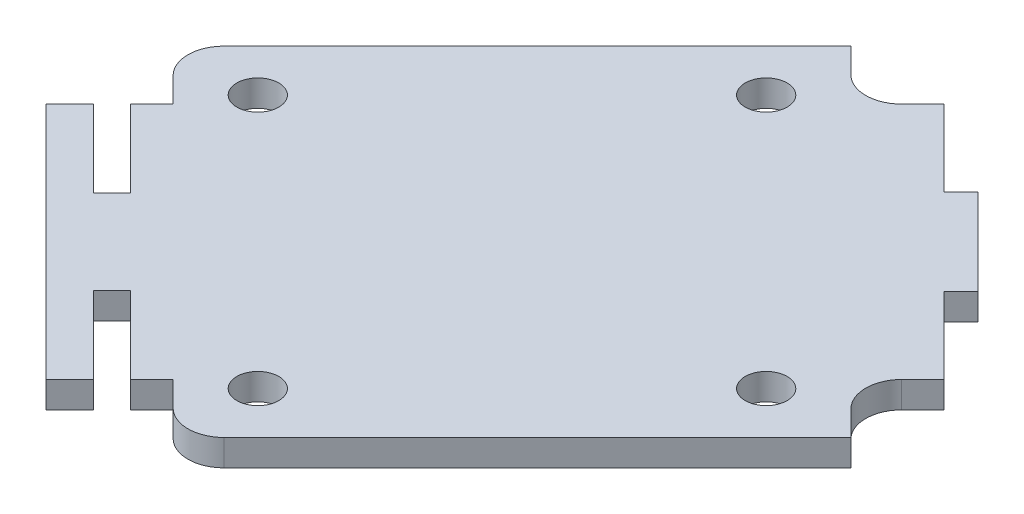
SolidWorks part; units mm, degrees
material "cardboard"
ref_plane "Front Plane" through (0, 0, 0) normal (0, 0, 1) x (1, 0, 0)
ref_plane "Top Plane" through (0, 0, 0) normal (0, 1, 0) x (1, 0, 0)
ref_plane "Right Plane" through (0, 0, 0) normal (1, 0, 0) x (0, 0, -1)
sketch "Sketch1" plane through (0, 0, 0) normal (0, 1, 0) x (1, 0, 0)
  line L0 (-132.1728, 126.9012) -> (-121.1728, 126.9012)
  line L1 (-122.1728, 122.9012) -> (-122.1728, 106.9012)
  line L2 (-62.3728, 122.9012) -> (-62.3728, 106.9012)
  line L3 (-119.7728, 106.9012) -> (-122.1728, 106.9012)
  line L4 (-133.5728, 122.9012) -> (-131.1728, 122.9012)
  line L5 (-133.5728, 122.9012) -> (-133.5728, 106.9012)
  line L6 (-133.5728, 106.9012) -> (-131.1728, 106.9012)
  line L7 (-131.1728, 122.9012) -> (-131.1728, 106.9012)
  line L8 (-119.7728, 122.9012) -> (-119.7728, 106.9012)
  line L9 (-119.7728, 122.9012) -> (-122.1728, 122.9012)
  line L10 (-59.9728, 122.9012) -> (-59.9728, 106.9012)
  line L11 (-96.5728, 126.9012) -> (-85.5728, 126.9012)
  line L12 (-62.3728, 122.9012) -> (-59.9728, 122.9012)
  line L13 (-62.3728, 106.9012) -> (-59.9728, 106.9012)
  line L14 (-50.9728, 122.9012) -> (-50.9728, 106.9012)
  line L15 (-48.5728, 122.9012) -> (-50.9728, 122.9012)
  line L16 (-48.5728, 122.9012) -> (-48.5728, 106.9012)
  line L17 (-48.5728, 106.9012) -> (-50.9728, 106.9012)
  line L18 (8.8272, 122.9012) -> (8.8272, 106.9012)
  line L19 (11.2272, 122.9012) -> (11.2272, 106.9012)
  line L20 (8.8272, 122.9012) -> (11.2272, 122.9012)
  line L21 (8.8272, 106.9012) -> (11.2272, 106.9012)
  line L22 (20.2272, 122.9012) -> (20.2272, 106.9012)
  line L23 (22.6272, 122.9012) -> (20.2272, 122.9012)
  line L24 (22.6272, 122.9012) -> (22.6272, 106.9012)
  line L25 (22.6272, 106.9012) -> (20.2272, 106.9012)
  line L26 (80.0272, 122.9012) -> (80.0272, 106.9012)
  line L27 (82.4272, 122.9012) -> (82.4272, 106.9012)
  line L28 (-60.9728, 126.9012) -> (-49.9728, 126.9012)
  line L29 (80.0272, 122.9012) -> (82.4272, 122.9012)
  line L30 (80.0272, 106.9012) -> (82.4272, 106.9012)
  line L31 (91.4272, 122.9012) -> (91.4272, 106.9012)
  line L32 (56.8272, 128.9012) -> (81.4272, 128.9012)
  line L33 (93.8272, 122.9012) -> (91.4272, 122.9012)
  line L34 (93.8272, 122.9012) -> (93.8272, 106.9012)
  line L35 (93.8272, 106.9012) -> (91.4272, 106.9012)
  line L36 (62.8843, 36.8646) -> (69.3002, 30.4488)
  line L37 (82.7871, 16.9619) -> (84.767, 18.9418)
  line L38 (62.8843, 36.8646) -> (64.8642, 38.8445)
  line L39 (76.3712, 23.3777) -> (82.7871, 16.9619)
  line L40 (82.7871, -85.8891) -> (76.3712, -92.305)
  line L41 (82.7871, -85.8891) -> (84.767, -87.869)
  line L42 (84.767, -87.869) -> (64.8642, -107.7718)
  line L43 (62.8843, -105.7919) -> (64.8642, -107.7718)
  line L44 (69.3002, -99.376) -> (62.8843, -105.7919)
  line L45 (-39.9666, -105.7919) -> (-46.3825, -99.376)
  line L46 (-39.9666, -105.7919) -> (-41.9465, -107.7718)
  line L47 (-41.9465, -107.7718) -> (-61.8493, -87.869)
  line L48 (-59.8694, -85.8891) -> (-61.8493, -87.869)
  line L49 (-53.4536, -92.305) -> (-59.8694, -85.8891)
  line L50 (-25.3728, 126.9012) -> (-14.3728, 126.9012)
  line L51 (10.2272, 126.9012) -> (21.2272, 126.9012)
  line L52 (45.8272, 126.9012) -> (56.8272, 126.9012)
  line L53 (81.4272, 126.9012) -> (92.4272, 126.9012)
  line L54 (117.0272, 126.9012) -> (128.0272, 126.9012)
  line L55 (-36.6432, -102.4685) -> (-34.5738, -104.5379)
  line L56 (-6.2376, -76.3055) -> (-4.1682, -78.3749)
  line L57 (-56.546, -82.5657) -> (-58.3138, -84.3335)
  line L58 (-36.6432, -102.4685) -> (-38.411, -104.2362)
  line L59 (-32.4525, -50.0907) -> (-58.6154, -76.2536)
  line L60 (-58.6154, -80.4963) -> (-56.546, -82.5657)
  line L61 (-4.1682, -78.3749) -> (-30.3312, -104.5379)
  line L62 (-32.4525, -50.0907) -> (-30.3831, -52.1601)
  line L63 (-144.4728, 128.9012) -> (-132.1728, 128.9012)
  line L64 (-55.8571, 81.6029) -> (-55.8571, 86.6029)
  line L65 (-65.8571, 81.6029) -> (-65.8571, 86.6029)
  line L66 (-35.3072, 73.0909) -> (-31.7716, 76.6264)
  line L67 (-28.2361, 66.0198) -> (-24.7006, 69.5553)
  line L68 (-19.724, 45.4699) -> (-14.724, 45.4699)
  line L69 (-19.724, 35.4699) -> (-14.724, 35.4699)
  line L70 (-28.2361, 14.92) -> (-24.7006, 11.3845)
  line L71 (-35.3072, 7.8489) -> (-31.7716, 4.3134)
  line L72 (-55.8571, -0.6631) -> (-55.8571, -5.6631)
  line L73 (-65.8571, -0.6631) -> (-65.8571, -5.6631)
  line L74 (-86.407, 7.8489) -> (-89.9425, 4.3134)
  line L75 (61.3287, 35.309) -> (67.7445, 28.8931)
  line L76 (74.8156, 21.8221) -> (81.2315, 15.4062)
  line L77 (74.8156, 21.8221) -> (76.3712, 23.3777)
  line L78 (67.7445, 28.8931) -> (69.3002, 30.4488)
  line L79 (29.5322, -78.0966) -> (32.3607, -75.2682)
  line L80 (55.0919, -16.3902) -> (52.2634, -13.5618)
  line L81 (-144.4728, 128.9012) -> (-144.4728, 118.9012)
  line L82 (-6.6146, 9.1694) -> (-32.1742, -16.3902)
  line L83 (-144.4728, 100.9012) -> (-128.6728, 100.9012)
  line L84 (-93.4781, 14.92) -> (-97.0136, 11.3845)
  line L85 (-108.8728, 119.9012) -> (-108.8728, 109.9012)
  line L86 (64.8642, 38.8445) -> (84.767, 18.9418)
  line L87 (-22.9584, -48.9781) -> (-3.0557, -68.8809)
  line L88 (-22.9584, -48.9781) -> (-26.1404, -52.1601)
  line L89 (-3.0557, -68.8809) -> (-6.2376, -72.0629)
  line L90 (-32.1742, -16.3902) -> (-67.1742, -16.3902)
  line L91 (-82.1742, -31.3902) -> (-82.1742, -37.537)
  line L92 (-67.1742, -52.537) -> (-34.8988, -52.537)
  line L93 (-112.1728, 105.9012) -> (-114.6728, 105.9012)
  line L94 (-141.1728, 125.9012) -> (-138.6728, 125.9012)
  line L95 (-141.1728, 125.9012) -> (-141.1728, 105.9012)
  line L96 (-141.1728, 105.9012) -> (-138.6728, 105.9012)
  line L97 (-138.6728, 125.9012) -> (-138.6728, 105.9012)
  line L98 (-114.6728, 125.9012) -> (-114.6728, 105.9012)
  line L99 (29.5322, 9.1694) -> (29.5322, 44.1694)
  line L100 (14.5322, 59.1694) -> (8.3854, 59.1694)
  line L101 (-6.6146, 44.1694) -> (-6.6146, 9.1694)
  line L102 (-112.1728, 125.9012) -> (-114.6728, 125.9012)
  line L103 (-112.1728, 125.9012) -> (-112.1728, 105.9012)
  line L104 (-124.6728, 100.9012) -> (-110.3728, 100.9012)
  line L105 (-108.8728, 119.9012) -> (-108.8728, 109.9012)
  line L106 (55.0919, -52.537) -> (90.0919, -52.537)
  line L107 (105.0919, -37.537) -> (105.0919, -31.3902)
  line L108 (90.0919, -16.3902) -> (55.0919, -16.3902)
  line L109 (-74.7728, 100.9012) -> (-73.2728, 100.9012)
  line L110 (-73.2728, 128.9012) -> (-73.2728, 100.9012)
  line L111 (21.2272, 128.9012) -> (45.8272, 128.9012)
  line L112 (-73.2728, 128.9012) -> (-73.2728, 100.9012)
  line L113 (-73.2728, 100.9012) -> (-37.6728, 100.9012)
  line L114 (-37.6728, 128.9012) -> (-37.6728, 100.9012)
  line L115 (-6.6146, -80.8213) -> (-6.6146, -113.0966)
  line L116 (8.3854, -128.0966) -> (14.5322, -128.0966)
  line L117 (29.5322, -113.0966) -> (29.5322, -78.0966)
  line L118 (-14.3728, 128.9012) -> (10.2272, 128.9012)
  line L119 (-37.6728, 128.9012) -> (-37.6728, 100.9012)
  line L120 (-37.6728, 100.9012) -> (-2.0728, 100.9012)
  line L121 (-2.0728, 128.9012) -> (-2.0728, 100.9012)
  line L122 (-49.9728, 128.9012) -> (-25.3728, 128.9012)
  line L123 (-2.0728, 128.9012) -> (-2.0728, 100.9012)
  line L124 (52.2634, -55.3654) -> (55.0919, -52.537)
  line L125 (25.9733, -68.8809) -> (45.8761, -48.9781)
  line L126 (81.2315, -84.3335) -> (74.8156, -90.7493)
  line L127 (45.8761, -48.9781) -> (81.2315, -84.3335)
  line L128 (74.8156, -90.7493) -> (76.3712, -92.305)
  line L129 (78.3511, -94.2849) -> (71.2801, -101.3559)
  line L130 (25.9733, -68.8809) -> (61.3287, -104.2362)
  line L131 (67.7445, -97.8204) -> (69.3002, -99.376)
  line L132 (67.7445, -97.8204) -> (61.3287, -104.2362)
  line L133 (-38.411, -104.2362) -> (-44.8269, -97.8204)
  line L134 (-44.8269, -97.8204) -> (-46.3825, -99.376)
  line L135 (32.3607, 6.341) -> (29.5322, 9.1694)
  line L136 (-101.9901, 35.4699) -> (-106.9901, 35.4699)
  line L137 (45.8761, -19.9491) -> (25.9733, -0.0463)
  line L138 (45.8761, -19.9491) -> (81.2315, 15.4062)
  line L139 (25.9733, -0.0463) -> (61.3287, 35.309)
  line L140 (-48.3624, -101.3559) -> (-55.4335, -94.2849)
  line L141 (-51.8979, -90.7493) -> (-53.4536, -92.305)
  line L142 (-51.8979, -90.7493) -> (-58.3138, -84.3335)
  line L143 (-65.8571, 81.6029) -> (-77.8949, 81.6029)
  line L144 (-77.8949, 81.6029) -> (-86.407, 73.0909)
  line L145 (-2.0728, 100.9012) -> (33.5272, 100.9012)
  line L146 (33.5272, 128.9012) -> (33.5272, 100.9012)
  line L147 (-85.5728, 128.9012) -> (-60.9728, 128.9012)
  line L148 (33.5272, 128.9012) -> (33.5272, 100.9012)
  line L149 (33.5272, 100.9012) -> (69.1272, 100.9012)
  line L150 (69.1272, 128.9012) -> (69.1272, 100.9012)
  line L151 (-121.1728, 128.9012) -> (-110.3728, 128.9012)
  line L152 (69.1272, 128.9012) -> (69.1272, 100.9012)
  line L153 (69.1272, 100.9012) -> (104.7272, 100.9012)
  line L154 (104.7272, 128.9012) -> (104.7272, 100.9012)
  line L155 (128.0272, 128.9012) -> (140.3272, 128.9012)
  line L156 (104.7272, 128.9012) -> (104.7272, 100.9012)
  line L157 (104.7272, 100.9012) -> (140.3272, 100.9012)
  line L158 (140.3272, 128.9012) -> (140.3272, 118.9012)
  line L159 (-69.9728, 125.9012) -> (-67.4728, 125.9012)
  line L160 (-69.9728, 125.9012) -> (-69.9728, 105.9012)
  line L161 (-69.9728, 105.9012) -> (-67.4728, 105.9012)
  line L162 (-67.4728, 125.9012) -> (-67.4728, 105.9012)
  line L163 (-43.4728, 125.9012) -> (-43.4728, 105.9012)
  line L164 (-40.9728, 105.9012) -> (-43.4728, 105.9012)
  line L165 (-40.9728, 125.9012) -> (-40.9728, 105.9012)
  line L166 (-40.9728, 125.9012) -> (-43.4728, 125.9012)
  line L167 (-61.4728, 100.9012) -> (-61.4728, 96.9012)
  line L168 (-61.4728, 96.9012) -> (-49.4728, 96.9012)
  line L169 (-49.4728, 96.9012) -> (-49.4728, 100.9012)
  line L170 (1.2272, 125.9012) -> (3.7272, 125.9012)
  line L171 (1.2272, 125.9012) -> (1.2272, 105.9012)
  line L172 (1.2272, 105.9012) -> (3.7272, 105.9012)
  line L173 (3.7272, 125.9012) -> (3.7272, 105.9012)
  line L174 (27.7272, 125.9012) -> (27.7272, 105.9012)
  line L175 (30.2272, 105.9012) -> (27.7272, 105.9012)
  line L176 (30.2272, 125.9012) -> (30.2272, 105.9012)
  line L177 (30.2272, 125.9012) -> (27.7272, 125.9012)
  line L178 (9.7272, 100.9012) -> (9.7272, 96.9012)
  line L179 (9.7272, 96.9012) -> (21.7272, 96.9012)
  line L180 (21.7272, 96.9012) -> (21.7272, 100.9012)
  line L181 (72.4272, 125.9012) -> (74.9272, 125.9012)
  line L182 (72.4272, 125.9012) -> (72.4272, 105.9012)
  line L183 (72.4272, 105.9012) -> (74.9272, 105.9012)
  line L184 (74.9272, 125.9012) -> (74.9272, 105.9012)
  line L185 (98.9272, 125.9012) -> (98.9272, 105.9012)
  line L186 (101.4272, 105.9012) -> (98.9272, 105.9012)
  line L187 (101.4272, 125.9012) -> (101.4272, 105.9012)
  line L188 (101.4272, 125.9012) -> (98.9272, 125.9012)
  line L189 (80.9272, 100.9012) -> (80.9272, 96.9012)
  line L190 (80.9272, 96.9012) -> (92.9272, 96.9012)
  line L191 (92.9272, 96.9012) -> (92.9272, 100.9012)
  line L192 (-128.6728, 100.9012) -> (-128.6728, 101.9012)
  line L193 (-128.6728, 101.9012) -> (-124.6728, 101.9012)
  line L194 (-124.6728, 101.9012) -> (-124.6728, 100.9012)
  line L195 (-61.4728, 99.9012) -> (-57.4728, 99.9012)
  line L196 (-57.4728, 99.9012) -> (-57.4728, 101.9012)
  line L197 (-57.4728, 101.9012) -> (-53.4728, 101.9012)
  line L198 (-53.4728, 101.9012) -> (-53.4728, 99.9012)
  line L199 (-53.4728, 99.9012) -> (-49.4728, 99.9012)
  line L200 (9.7272, 99.9012) -> (13.7272, 99.9012)
  line L201 (13.7272, 99.9012) -> (13.7272, 101.9012)
  line L202 (13.7272, 101.9012) -> (17.7272, 101.9012)
  line L203 (27.3876, 1.3679) -> (33.7515, -4.9961)
  line L204 (33.7515, -4.9961) -> (30.9231, -7.8245)
  line L205 (30.9231, -7.8245) -> (38.098, -14.9994)
  line L206 (38.098, -14.9994) -> (40.9264, -12.1709)
  line L207 (40.9264, -12.1709) -> (47.2903, -18.5349)
  line L208 (47.2903, -50.3923) -> (40.9264, -56.7563)
  line L209 (40.9264, -56.7563) -> (38.098, -53.9279)
  line L210 (38.098, -53.9279) -> (30.9231, -61.1027)
  line L211 (30.9231, -61.1027) -> (33.7515, -63.9312)
  line L212 (33.7515, -63.9312) -> (27.3876, -70.2951)
  line L213 (-4.4699, -70.2951) -> (-10.8338, -63.9312)
  line L214 (-10.8338, -63.9312) -> (-8.0054, -61.1027)
  line L215 (-8.0054, -61.1027) -> (-15.1803, -53.9279)
  line L216 (-15.1803, -53.9279) -> (-18.0087, -56.7563)
  line L217 (-18.0087, -56.7563) -> (-24.3727, -50.3923)
  line L218 (-89.9425, 76.6264) -> (-97.0136, 69.5553)
  line L219 (-93.4781, 66.0198) -> (-101.9901, 57.5078)
  line L220 (-101.9901, 57.5078) -> (-101.9901, 45.4699)
  line L221 (-106.9901, 45.4699) -> (-106.9901, 35.4699)
  line L222 (-101.9901, 35.4699) -> (-101.9901, 23.432)
  line L223 (-101.9901, 23.432) -> (-93.4781, 14.92)
  line L224 (-97.0136, 11.3845) -> (-89.9425, 4.3134)
  line L225 (-86.407, 7.8489) -> (-77.8949, -0.6631)
  line L226 (-77.8949, -0.6631) -> (-65.8571, -0.6631)
  line L227 (-65.8571, -5.6631) -> (-55.8571, -5.6631)
  line L228 (-55.8571, -0.6631) -> (-43.8192, -0.6631)
  line L229 (-43.8192, -0.6631) -> (-35.3072, 7.8489)
  line L230 (-31.7716, 4.3134) -> (-24.7006, 11.3845)
  line L231 (-28.2361, 14.92) -> (-19.724, 23.432)
  line L232 (-19.724, 23.432) -> (-19.724, 35.4699)
  line L233 (-14.724, 35.4699) -> (-14.724, 45.4699)
  line L234 (-19.724, 45.4699) -> (-19.724, 57.5078)
  line L235 (-19.724, 57.5078) -> (-28.2361, 66.0198)
  line L236 (-24.7006, 69.5553) -> (-31.7716, 76.6264)
  line L237 (-35.3072, 73.0909) -> (-43.8192, 81.6029)
  line L238 (-43.8192, 81.6029) -> (-55.8571, 81.6029)
  line L239 (-55.8571, 86.6029) -> (-65.8571, 86.6029)
  line L240 (-101.9901, 45.4699) -> (-106.9901, 45.4699)
  line L241 (-93.4781, 66.0198) -> (-97.0136, 69.5553)
  line L242 (-86.407, 73.0909) -> (-89.9425, 76.6264)
  line L243 (17.7272, 101.9012) -> (17.7272, 99.9012)
  line L244 (17.7272, 99.9012) -> (21.7272, 99.9012)
  line L245 (80.9272, 99.9012) -> (84.9272, 99.9012)
  line L246 (84.9272, 99.9012) -> (84.9272, 101.9012)
  line L247 (84.9272, 101.9012) -> (88.9272, 101.9012)
  line L248 (88.9272, 101.9012) -> (88.9272, 99.9012)
  line L249 (88.9272, 99.9012) -> (92.9272, 99.9012)
  line L250 (140.3272, 118.9012) -> (142.3272, 118.9012)
  line L251 (142.3272, 110.9012) -> (140.3272, 110.9012)
  line L252 (140.3272, 110.9012) -> (140.3272, 100.9012)
  line L253 (-144.4728, 118.9012) -> (-143.4728, 118.9012)
  line L254 (-143.4728, 118.9012) -> (-143.4728, 110.9012)
  line L255 (-143.4728, 110.9012) -> (-144.4728, 110.9012)
  line L256 (-144.4728, 110.9012) -> (-144.4728, 100.9012)
  line L257 (-110.3728, 128.9012) -> (-110.3728, 119.9012)
  line L258 (-110.3728, 119.9012) -> (-108.8728, 119.9012)
  line L259 (-108.8728, 109.9012) -> (-110.3728, 109.9012)
  line L260 (-110.3728, 109.9012) -> (-110.3728, 100.9012)
  line L261 (-74.7728, 128.9012) -> (-74.7728, 119.9012)
  line L262 (-74.7728, 119.9012) -> (-71.7728, 119.9012)
  line L263 (-71.7728, 119.9012) -> (-71.7728, 109.9012)
  line L264 (-71.7728, 109.9012) -> (-74.7728, 109.9012)
  line L265 (-74.7728, 109.9012) -> (-74.7728, 100.9012)
  line L266 (-39.1728, 128.9012) -> (-39.1728, 119.9012)
  line L267 (-39.1728, 119.9012) -> (-36.1728, 119.9012)
  line L268 (-36.1728, 119.9012) -> (-36.1728, 109.9012)
  line L269 (-36.1728, 109.9012) -> (-39.1728, 109.9012)
  line L270 (-39.1728, 109.9012) -> (-39.1728, 100.9012)
  line L271 (-3.5728, 128.9012) -> (-3.5728, 119.9012)
  line L272 (-3.5728, 119.9012) -> (-0.5728, 119.9012)
  line L273 (-0.5728, 119.9012) -> (-0.5728, 109.9012)
  line L274 (-0.5728, 109.9012) -> (-3.5728, 109.9012)
  line L275 (-3.5728, 109.9012) -> (-3.5728, 100.9012)
  line L276 (32.0272, 128.9012) -> (32.0272, 119.9012)
  line L277 (32.0272, 119.9012) -> (35.0272, 119.9012)
  line L278 (35.0272, 119.9012) -> (35.0272, 109.9012)
  line L279 (35.0272, 109.9012) -> (32.0272, 109.9012)
  line L280 (32.0272, 109.9012) -> (32.0272, 100.9012)
  line L281 (67.6272, 128.9012) -> (67.6272, 119.9012)
  line L282 (67.6272, 119.9012) -> (70.6272, 119.9012)
  line L283 (70.6272, 119.9012) -> (70.6272, 109.9012)
  line L284 (70.6272, 109.9012) -> (67.6272, 109.9012)
  line L285 (67.6272, 109.9012) -> (67.6272, 100.9012)
  line L286 (103.2272, 128.9012) -> (103.2272, 119.9012)
  line L287 (103.2272, 119.9012) -> (106.2272, 119.9012)
  line L288 (106.2272, 119.9012) -> (106.2272, 109.9012)
  line L289 (106.2272, 109.9012) -> (103.2272, 109.9012)
  line L290 (103.2272, 109.9012) -> (103.2272, 100.9012)
  line L291 (142.3272, 118.9012) -> (142.3272, 110.9012)
  line L292 (-132.1728, 128.9012) -> (-132.1728, 126.9012)
  line L293 (-121.1728, 128.9012) -> (-121.1728, 126.9012)
  line L294 (-96.5728, 128.9012) -> (-96.5728, 126.9012)
  line L295 (-85.5728, 128.9012) -> (-85.5728, 126.9012)
  line L296 (-60.9728, 128.9012) -> (-60.9728, 126.9012)
  line L297 (-49.9728, 128.9012) -> (-49.9728, 126.9012)
  line L298 (-25.3728, 128.9012) -> (-25.3728, 126.9012)
  line L299 (-14.3728, 128.9012) -> (-14.3728, 126.9012)
  line L300 (10.2272, 128.9012) -> (10.2272, 126.9012)
  line L301 (21.2272, 128.9012) -> (21.2272, 126.9012)
  line L302 (45.8272, 128.9012) -> (45.8272, 126.9012)
  line L303 (56.8272, 128.9012) -> (56.8272, 126.9012)
  line L304 (81.4272, 128.9012) -> (81.4272, 126.9012)
  line L305 (92.4272, 128.9012) -> (92.4272, 126.9012)
  line L306 (117.0272, 128.9012) -> (117.0272, 126.9012)
  line L307 (128.0272, 128.9012) -> (128.0272, 126.9012)
  line L308 (92.4272, 128.9012) -> (117.0272, 128.9012)
  circle A0 centre (-32.4525, -57.1617) radius 1.75
  circle A1 centre (-60.8571, 67.4699) radius 6
  circle A2 centre (-41.7652, 59.5618) radius 6
  circle A3 centre (-33.8571, 40.4699) radius 6
  circle A4 centre (-11.2393, -78.3749) radius 1.75
  circle A5 centre (-32.4525, -99.5882) radius 1.75
  circle A6 centre (11.4588, 34.1694) radius 10
  circle A7 centre (-126.6728, 113.4012) radius 1
  circle A8 centre (-53.6657, -78.3749) radius 1.75
  arc A9 (-30.3831, -52.1601) -> (-26.1404, -52.1601) centre (-28.2617, -50.0388) ccw
  arc A10 (-6.2376, -76.3055) -> (-6.2376, -72.0629) centre (-4.1163, -74.1842) cw
  circle A11 centre (-55.4728, 113.4012) radius 1
  circle A12 centre (80.0919, -34.4636) radius 10
  circle A13 centre (11.4588, -34.4636) radius 15
  arc A14 (-67.1742, -16.3902) -> (-82.1742, -31.3902) centre (-67.1742, -31.3902) ccw
  arc A15 (-82.1742, -37.537) -> (-67.1742, -52.537) centre (-67.1742, -37.537) ccw
  arc A16 (-6.6146, -113.0966) -> (8.3854, -128.0966) centre (8.3854, -113.0966) ccw
  arc A17 (14.5322, -128.0966) -> (29.5322, -113.0966) centre (14.5322, -113.0966) ccw
  arc A18 (90.0919, -52.537) -> (105.0919, -37.537) centre (90.0919, -37.537) ccw
  arc A19 (105.0919, -31.3902) -> (90.0919, -16.3902) centre (90.0919, -31.3902) ccw
  arc A20 (29.5322, 44.1694) -> (14.5322, 59.1694) centre (14.5322, 44.1694) ccw
  circle A21 centre (15.7272, 113.4012) radius 1
  circle A22 centre (11.4588, -103.0966) radius 10
  circle A23 centre (86.9272, 113.4012) radius 1
  circle A24 centre (-57.1742, -34.4636) radius 10
  circle A25 centre (-41.7652, 21.378) radius 6
  circle A26 centre (-91.0728, 114.9012) radius 7.5
  circle A27 centre (-19.8728, 114.9012) radius 7.5
  circle A28 centre (51.3272, 114.9012) radius 7.5
  circle A29 centre (122.5272, 114.9012) radius 7.5
  arc A30 (8.3854, 59.1694) -> (-6.6146, 44.1694) centre (8.3854, 44.1694) ccw
  arc A31 (-34.5738, -104.5379) -> (-30.3312, -104.5379) centre (-32.4525, -102.4166) ccw
  arc A32 (-58.6154, -76.2536) -> (-58.6154, -80.4963) centre (-56.4941, -78.3749) ccw
  circle A33 centre (-60.8571, 13.4699) radius 6
  circle A34 centre (-79.949, 21.378) radius 6
  circle A35 centre (-87.8571, 40.4699) radius 6
  circle A36 centre (-79.949, 59.5618) radius 6
  circle A37 centre (-60.8571, 40.4699) radius 15
  point P67 (11.4588, -34.4636)
  point P113 (11.4588, -34.4636)
  point P166 (11.4588, -34.4636)
  point P168 (11.4588, -34.4636)
  point P177 (11.4588, -34.4636)
  point P182 (11.4588, -34.4636)
  point P246 (11.4588, -34.4636)
  point P268 (11.4588, -34.4636)
  point P279 (11.4588, -34.4636)
  point P313 (-60.8571, 40.4699)
  point P314 (-60.8571, 40.4699)
  point P399 (-60.8571, 40.4699)
extrude "Boss-Extrude1" add sketch "Sketch1" along normal blind 2.2 contours L59 A32 L60 L57 L142 L141 L49 L48 L47 L46 L45 L134 L133 L58 L55 A31 L61 L56 A10 L89 L213 L214 L87 L216 L217 L88 A9 L62 A0 A4 A5 A8
